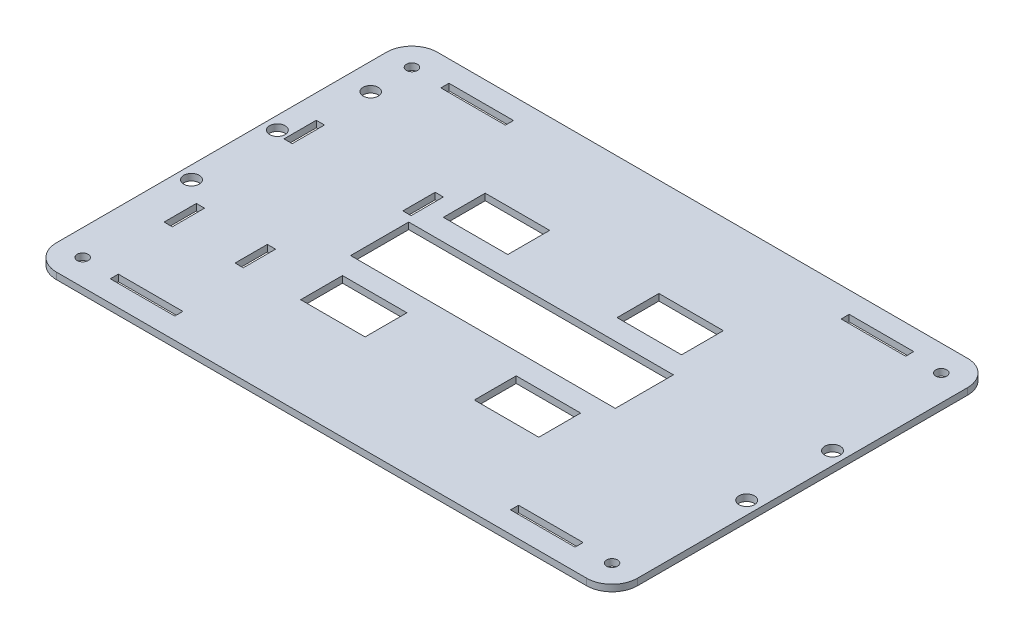
SolidWorks part; units mm, degrees
ref_plane "Front Plane" through (0, 0, 0) normal (0, 0, 1) x (1, 0, 0)
ref_plane "Top Plane" through (0, 0, 0) normal (0, 1, 0) x (1, 0, 0)
ref_plane "Right Plane" through (0, 0, 0) normal (1, 0, 0) x (0, 0, -1)
sketch "Sketch1" plane through (0, 0, 0) normal (0, 1, 0) x (1, 0, 0)
  line L0 (114.3, 0) -> (114.3, -149.86) construction
  line L1 (0, 0) -> (228.6, 0)
  line L2 (0, 0) -> (0, -149.86)
  line L3 (0, -149.86) -> (228.6, -149.86)
  line L4 (228.6, 0) -> (228.6, -149.86)
  line L5 (0, -74.93) -> (228.6, -74.93) construction
  line L6 (205.74, -11.4755) -> (180.34, -8.3005) construction
  line L7 (22.86, -8.3005) -> (48.26, -8.3005)
  line L8 (22.86, -8.3005) -> (22.86, -11.4755)
  line L9 (22.86, -11.4755) -> (48.26, -11.4755)
  line L10 (48.26, -8.3005) -> (48.26, -11.4755)
  line L11 (22.86, -8.3005) -> (48.26, -11.4755) construction
  line L12 (22.86, -11.4755) -> (48.26, -8.3005) construction
  line L13 (205.74, -8.3005) -> (180.34, -11.4755) construction
  line L14 (180.34, -8.3005) -> (180.34, -11.4755)
  line L15 (205.74, -11.4755) -> (180.34, -11.4755)
  line L16 (205.74, -8.3005) -> (205.74, -11.4755)
  line L17 (205.74, -8.3005) -> (180.34, -8.3005)
  line L18 (205.74, -141.5595) -> (180.34, -138.3845) construction
  line L19 (205.74, -138.3845) -> (180.34, -141.5595) construction
  line L20 (205.74, -141.5595) -> (180.34, -141.5595)
  line L21 (205.74, -141.5595) -> (205.74, -138.3845)
  line L22 (205.74, -138.3845) -> (180.34, -138.3845)
  line L23 (180.34, -141.5595) -> (180.34, -138.3845)
  line L24 (22.86, -138.3845) -> (48.26, -141.5595) construction
  line L25 (22.86, -141.5595) -> (48.26, -138.3845) construction
  line L26 (48.26, -141.5595) -> (48.26, -138.3845)
  line L27 (22.86, -138.3845) -> (48.26, -138.3845)
  line L28 (22.86, -141.5595) -> (22.86, -138.3845)
  line L29 (22.86, -141.5595) -> (48.26, -141.5595)
  line L30 (5.08, -58.039) -> (5.08, -91.821) construction
  circle A0 centre (5.08, -58.039) radius 3.05
  circle A1 centre (5.08, -91.821) radius 3.05
  circle A2 centre (223.52, -91.821) radius 3.05
  circle A3 centre (223.52, -58.039) radius 3.05
  circle A4 centre (218.44, -10.16) radius 2.159
  circle A5 centre (10.16, -10.16) radius 2.159
  circle A6 centre (218.44, -139.7) radius 2.159
  circle A7 centre (10.16, -139.7) radius 2.159
  point P25 (35.56, -9.888)
  point P34 (193.04, -9.888)
  point P39 (193.04, -139.972)
  point P44 (35.56, -139.972)
  point P45 (5.08, -74.93)
  point P46 (0, 0)
  point P47 (0, 0)
  point P48 (0, 0)
  point P49 (0, 0)
  dimension "D3" = 5.08
  dimension "D4" = 33.782
  dimension "D6" = 6.1
  dimension "D1" = 149.86
  dimension "D2" = 228.6
  dimension "D7" = 10.16
  dimension "D8" = 10.16
  dimension "D9" = 3.175
  dimension "D10" = 25.4
  dimension "D11" = 25.4
extrude "Boss-Extrude1" add sketch "Sketch1" along normal blind 2.6 contours L10 L7 L8 L9 | A5 | A0 | A1 | A7 | L28 L29 L26 L27 | A6 | L23 L20 L21 L22 | A2 | A3 | A4 | L16 L17 L14 L15 | L1 L4 L3 L2
fillet "Fillet1" radius 10 4 edges at (0, 1.3, 0) (0, 1.3, 149.86) (228.6, 1.3, 149.86) (228.6, 1.3, 0)
sketch "Sketch25" plane through (0, 2.6, 0) normal (0, 1, 0) x (1, 0, 0)
  line L0 (114.3, 0) -> (114.3, -149.86) construction
  line L1 (62.23, -86.36) -> (166.37, -86.36)
  line L2 (62.23, -86.36) -> (62.23, -63.5)
  line L3 (62.23, -63.5) -> (166.37, -63.5)
  line L4 (166.37, -86.36) -> (166.37, -63.5)
  line L5 (10, 0) -> (218.6, 0) construction
  line L6 (10, -149.86) -> (218.6, -149.86) construction
  line L7 (0, -74.93) -> (228.6, -74.93) construction
  line L8 (0, -10) -> (0, -139.86) construction
  line L9 (228.6, -10) -> (228.6, -139.86) construction
  line L10 (9.3722, -53.364) -> (12.6107, -53.364) construction
  line L11 (9.3722, -47.014) -> (12.6107, -47.014)
  line L12 (9.3722, -47.014) -> (9.3722, -59.714)
  line L13 (9.3722, -59.714) -> (12.6107, -59.714)
  line L14 (12.6107, -47.014) -> (12.6107, -59.714)
  line L15 (57.2893, -48.157) -> (60.5278, -48.157)
  line L16 (57.2893, -48.157) -> (57.2893, -60.857)
  line L17 (57.2893, -60.857) -> (60.5278, -60.857)
  line L18 (60.5278, -48.157) -> (60.5278, -60.857)
  line L19 (14.122, -111.6443) -> (17.3605, -111.6443)
  line L20 (14.122, -111.6443) -> (14.122, -98.9443)
  line L21 (14.122, -98.9443) -> (17.3605, -98.9443)
  line L22 (17.3605, -111.6443) -> (17.3605, -98.9443)
  line L23 (42.0493, -111.6443) -> (45.2878, -111.6443)
  line L24 (42.0493, -111.6443) -> (42.0493, -98.9443)
  line L25 (42.0493, -98.9443) -> (45.2878, -98.9443)
  line L26 (45.2878, -111.6443) -> (45.2878, -98.9443)
  line L27 (57.2893, -54.507) -> (60.5278, -54.507) construction
  line L28 (14.122, -105.2943) -> (17.3605, -105.2943) construction
  line L29 (42.0493, -105.2943) -> (45.2878, -105.2943) construction
  point P16 (114.3, -63.5)
  point P17 (166.37, -74.93)
  dimension "D3" = 12.7
  dimension "D1" = 104.14
  dimension "D2" = 22.86
extrude "Cut-Extrude18" cut sketch "Sketch25" against normal blind 10.16
sketch "Sketch26" plane through (0, 2.6, 0) normal (0, 1, 0) x (1, 0, 0)
  line L0 (0, -74.93) -> (228.6, -74.93) construction
  line L1 (67.4474, -55.0884) -> (92.8063, -55.0884)
  line L2 (67.4474, -55.0884) -> (67.4474, -38.6191)
  line L3 (67.4474, -38.6191) -> (92.8063, -38.6191)
  line L4 (92.8063, -55.0884) -> (92.8063, -38.6191)
  line L5 (0, -10) -> (0, -139.86) construction
  line L6 (228.6, -10) -> (228.6, -139.86) construction
  line L7 (92.8063, -94.7716) -> (92.8063, -111.2409)
  line L8 (67.4474, -111.2409) -> (92.8063, -111.2409)
  line L9 (67.4474, -94.7716) -> (67.4474, -111.2409)
  line L10 (67.4474, -94.7716) -> (92.8063, -94.7716)
  line L11 (114.3, 0) -> (114.3, -149.86) construction
  line L12 (10, 0) -> (218.6, 0) construction
  line L13 (10, -149.86) -> (218.6, -149.86) construction
  line L14 (161.1526, -94.7716) -> (135.7937, -94.7716)
  line L15 (161.1526, -94.7716) -> (161.1526, -111.2409)
  line L16 (161.1526, -111.2409) -> (135.7937, -111.2409)
  line L17 (135.7937, -94.7716) -> (135.7937, -111.2409)
  line L18 (135.7937, -55.0884) -> (135.7937, -38.6191)
  line L19 (161.1526, -38.6191) -> (135.7937, -38.6191)
  line L20 (161.1526, -55.0884) -> (161.1526, -38.6191)
  line L21 (161.1526, -55.0884) -> (135.7937, -55.0884)
extrude "Cut-Extrude19" cut sketch "Sketch26" against normal blind 7.62
sketch "Sketch27" plane through (0, 2.6, 0) normal (0, 1, 0) x (1, 0, 0)
  circle A0 centre (10.3569, -26.5872) radius 3
  point P2 (9.1268, -28.0633)
  point P3 (10.3569, -26.5872)
  dimension "D1" = 6
extrude "Cut-Extrude20" cut sketch "Sketch27" against normal blind 7.62
